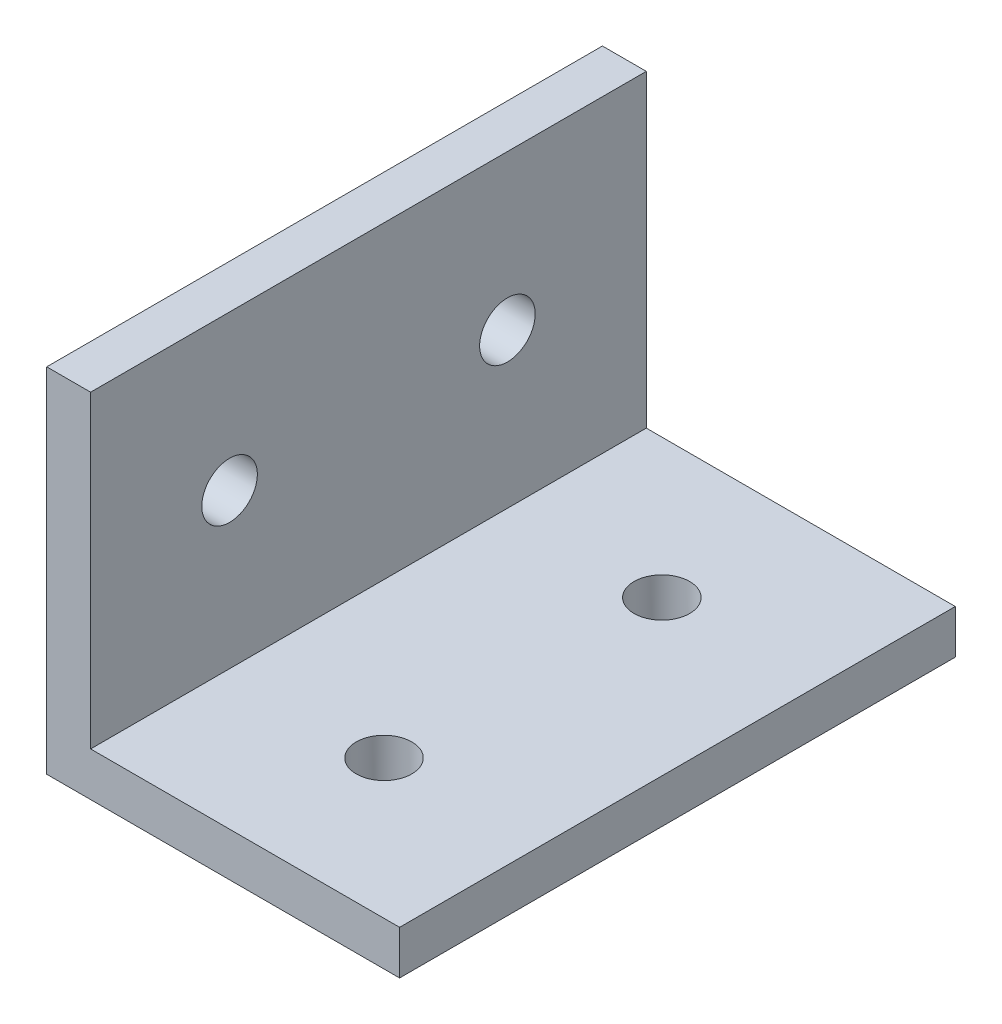
SolidWorks part; units mm, degrees
ref_plane "Front Plane" through (0, 0, 0) normal (0, 0, 1) x (1, 0, 0)
ref_plane "Top Plane" through (0, 0, 0) normal (0, 1, 0) x (1, 0, 0)
ref_plane "Right Plane" through (0, 0, 0) normal (1, 0, 0) x (0, 0, -1)
sketch "Sketch1" plane through (0, 0, 0) normal (0, 0, 1) x (1, 0, 0)
  line L0 (0, 0) -> (0, 12.7)
  line L1 (0, 0) -> (12.7, 0)
  line L2 (1.58, 1.58) -> (12.7, 1.58)
  line L3 (1.58, 1.58) -> (1.58, 12.7)
  line L4 (0, 12.7) -> (1.58, 12.7)
  line L5 (12.7, 1.58) -> (12.7, 0)
  dimension "D1" = 12.7
  dimension "D2" = 12.7
  dimension "D3" = 1.58
extrude "Boss-Extrude1" add sketch "Sketch1" along normal blind 20
sketch "Sketch2" plane through (0, 0, 0) normal (-1, 0, 0) x (0, 0, 1)
  line L0 (0, 1.58) -> (20, 1.58)
  line L1 (0, 12.7) -> (0, 0) construction
  line L2 (20, 12.7) -> (20, 0) construction
  line L3 (10, 1.58) -> (10, 12.7)
  line L4 (20, 12.7) -> (0, 12.7) construction
  line L5 (10, 7.14) -> (0, 7.14)
  line L6 (10, 7.14) -> (20, 7.14)
  circle A0 centre (5, 7.14) radius 1
  circle A1 centre (15, 7.14) radius 1
  dimension "D1" = 2
  dimension "D2" = 2
extrude "Cut-Extrude1" cut sketch "Sketch2" against normal up to next contours L5 A0 | L5 A0 | L6 A1 | L6 A1
pattern_circular "CirPattern1" count 2 every 90 about axis through (1.58, 1.58, 20) along (0, 0, -1) of "Cut-Extrude1"
